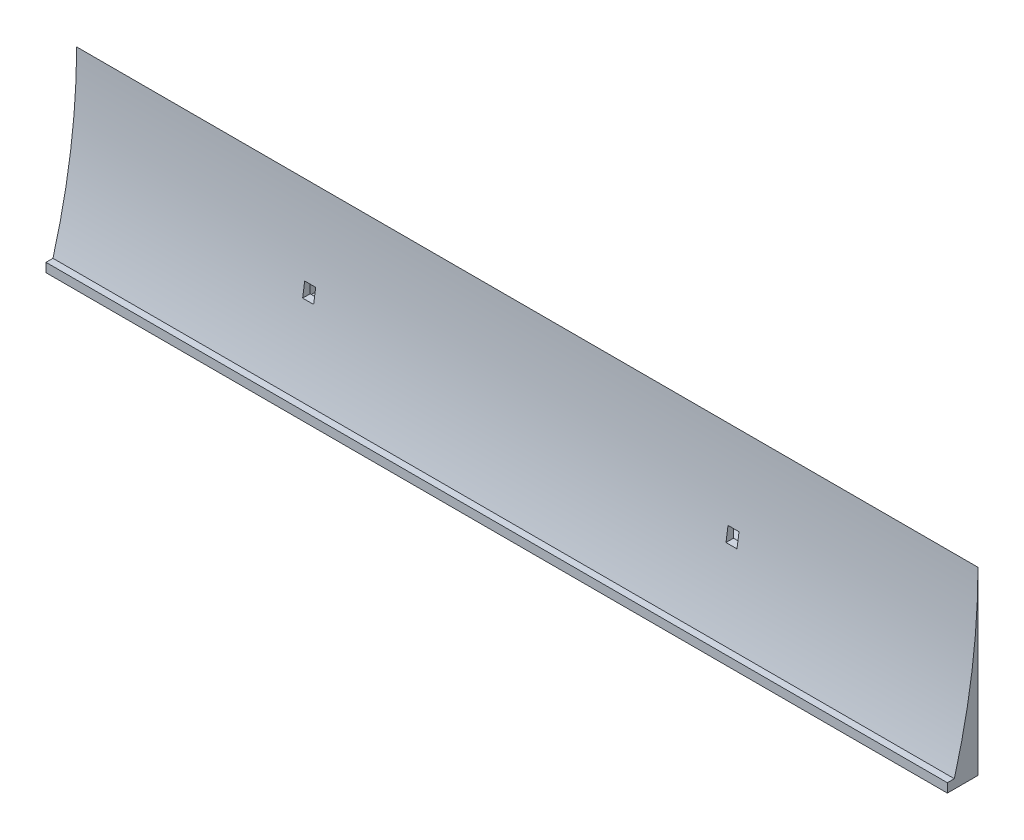
SolidWorks part; units mm, degrees
ref_plane "Plan de face" through (0, 0, 0) normal (0, 0, 1) x (1, 0, 0)
ref_plane "Plan de dessus" through (0, 0, 0) normal (0, 1, 0) x (1, 0, 0)
ref_plane "Plan de droite" through (0, 0, 0) normal (1, 0, 0) x (0, 0, -1)
sketch "Esquisse1" plane through (0, 0, 0) normal (0, 0, 1) x (1, 0, 0)
  line L1 (250, -50) -> (-250, -50)
  line L2 (250, -50) -> (250, 50)
  line L3 (250, 50) -> (-250, 50)
  line L4 (-250, -50) -> (-250, 50)
  line L5 (250, -50) -> (-250, 50) construction
  line L6 (250, 50) -> (-250, -50) construction
  point P0 (0, 0)
  dimension "D1" = 500
  dimension "D2" = 100
extrude "Boss.-Extru.1" add sketch "Esquisse1" along normal blind 20
sketch "Esquisse2" plane through (-250, 0, 0) normal (-1, 0, 0) x (0, 0, 1)
  line L0 (17, -50) -> (17, -45)
  line L1 (17, -45) -> (13.1395, -45)
  line L4 (0, 50) -> (0, -50)
  line L5 (0, -50) -> (20, -50)
  line L6 (20, -50) -> (20, 50)
  line L7 (20, 50) -> (0, 50)
  line L8 (0, 50) -> (0, -50)
  line L9 (0, -50) -> (20, -50)
  line L10 (20, -50) -> (20, 50)
  line L11 (20, 50) -> (0, 50)
  arc A0 (0, 50) -> (13.1395, -45) centre (350, 50) ccw
  line M8 (0, -50) -> (20, -50)
  line M9 (20, -50) -> (20, 50)
  line M10 (20, 50) -> (0, 50)
  dimension "D4" = 350
  dimension "D2" = 3
  dimension "D3" = 5
  dimension "D1" = 0
extrude "Enlèv. mat.-Extru.1" cut sketch "Esquisse2" against normal up to next contours A0 L1 L0 M10 M8 M9
sketch "Esquisse3" plane through (0, 0, 0) normal (0, 0, -1) x (-1, 0, 0)
  line L0 (0, 0) -> (0, 19.0283) construction
  line L1 (-114.368, 3.85) -> (-120.468, 3.85)
  line L2 (-114.368, 3.85) -> (-114.368, -3.85)
  line L3 (-114.368, -3.85) -> (-120.468, -3.85)
  line L4 (-120.468, 3.85) -> (-120.468, -3.85)
  line L5 (120.468, 3.85) -> (120.468, -3.85)
  line L6 (114.368, -3.85) -> (120.468, -3.85)
  line L7 (114.368, 3.85) -> (114.368, -3.85)
  line L8 (114.368, 3.85) -> (120.468, 3.85)
  point P4 (-114.368, 0)
  dimension "D1" = 6.1
  dimension "D2" = 7.7
extrude "Enlèv. mat.-Extru.2" cut sketch "Esquisse3" against normal blind 10
sketch "Esquisse4" plane through (0, 0, 0) normal (0, 0, 1) x (1, 0, 0)
  line L0 (0, 0) -> (0, -38.4971) construction
  line L1 (-100, -14.0503) -> (-130, -14.0503)
  line L2 (-100, -14.0503) -> (-100, 22.2958)
  line L3 (-100, 22.2958) -> (-130, 22.2958)
  line L4 (-130, -14.0503) -> (-130, 22.2958)
  line L5 (100, -14.0503) -> (130, -14.0503)
  line L6 (130, -14.0503) -> (130, 22.2958)
  line L7 (100, 22.2958) -> (130, 22.2958)
  line L8 (100, -14.0503) -> (100, 22.2958)
  line L9 (103, 19.2958) -> (127, 19.2958)
  line L10 (127, -11.0503) -> (127, 19.2958)
  line L11 (103, -11.0503) -> (127, -11.0503)
  line L12 (103, -11.0503) -> (103, 19.2958)
  line L13 (-103, -11.0503) -> (-103, 19.2958)
  line L14 (-103, 19.2958) -> (-127, 19.2958)
  line L15 (-127, -11.0503) -> (-127, 19.2958)
  line L16 (-103, -11.0503) -> (-127, -11.0503)
  dimension "D1" = 100
  dimension "D2" = 30
  dimension "D3" = 3
  dimension "D4" = 3
extrude "Boss.-Extru.2" add sketch "Esquisse4" against normal blind 25
ref_plane "Plan1" through (0, 0, -25) normal (0, 0, -1) x (-1, 0, 0)
sketch "Esquisse6" plane through (0, 0, -25) normal (0, 0, -1) x (-1, 0, 0)
  line L2 (-100, 22.2958) -> (-130, 22.2958)
  line L3 (-100, 22.2958) -> (-100, -14.0503)
  line L4 (-100, -14.0503) -> (-130, -14.0503)
  line L5 (-130, 22.2958) -> (-130, -14.0503)
extrude "Boss.-Extru.3" add sketch "Esquisse6" along normal blind 2
sketch "Esquisse7" plane through (0, 0, -25) normal (0, 0, -1) x (-1, 0, 0)
  line L1 (100, -14.0503) -> (130, -14.0503)
  line L2 (100, -14.0503) -> (100, 22.2958)
  line L3 (100, 22.2958) -> (130, 22.2958)
  line L4 (130, -14.0503) -> (130, 22.2958)
extrude "Boss.-Extru.4" add sketch "Esquisse7" along normal blind 2
